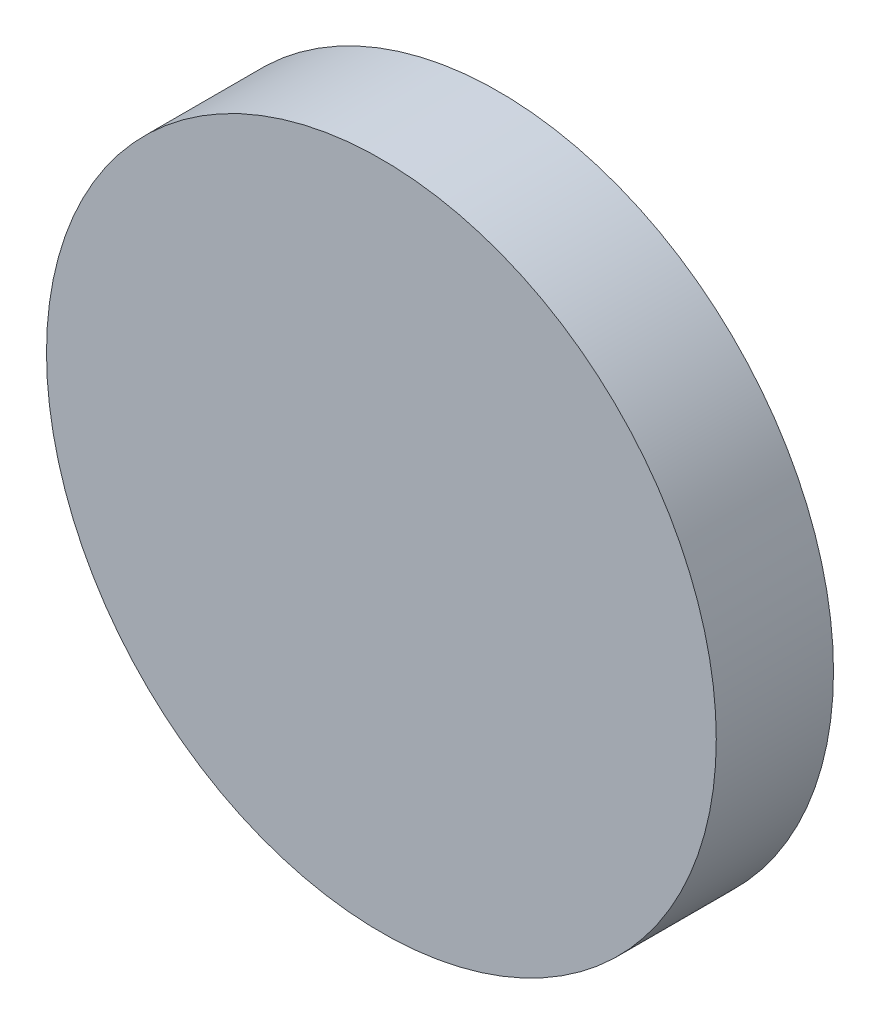
SolidWorks part; units mm, degrees
ref_plane "Front Plane" through (0, 0, 0) normal (0, 0, 1) x (1, 0, 0)
ref_plane "Top Plane" through (0, 0, 0) normal (0, 1, 0) x (1, 0, 0)
ref_plane "Right Plane" through (0, 0, 0) normal (1, 0, 0) x (0, 0, -1)
sketch "Sketch1" plane through (0, 0, 0) normal (0, 0, 1) x (1, 0, 0)
  circle A0 centre (0, 0) radius 20
  dimension "D1" = 40
extrude "Boss-Extrude1" add sketch "Sketch1" along normal blind 7
